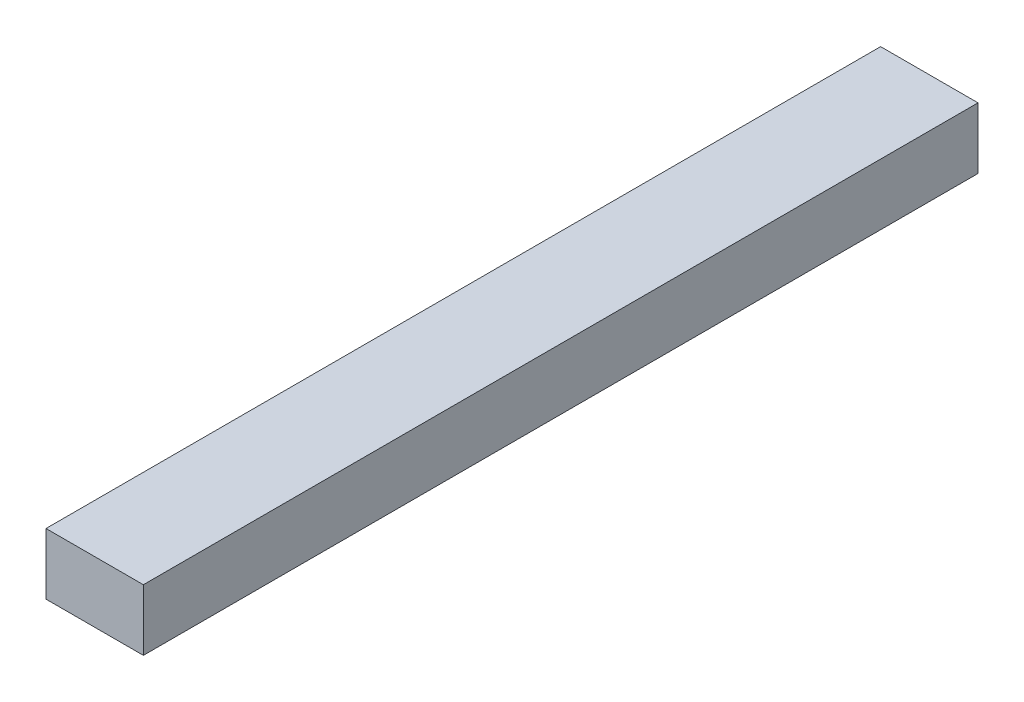
SolidWorks part; units mm, degrees
ref_plane "Front Plane" through (0, 0, 0) normal (0, 0, 1) x (1, 0, 0)
ref_plane "Top Plane" through (0, 0, 0) normal (0, 1, 0) x (1, 0, 0)
ref_plane "Right Plane" through (0, 0, 0) normal (1, 0, 0) x (0, 0, -1)
sketch "Sketch2" plane through (0, 0, 0) normal (0, 0, 1) x (1, 0, 0)
  line L1 (0, 0) -> (70, 0)
  line L2 (0, 0) -> (0, 44)
  line L3 (0, 44) -> (70, 44)
  line L4 (70, 0) -> (70, 44)
  dimension "D1" = 70
  dimension "D2" = 44
extrude "Extrude1" add sketch "Sketch2" along normal blind 600
